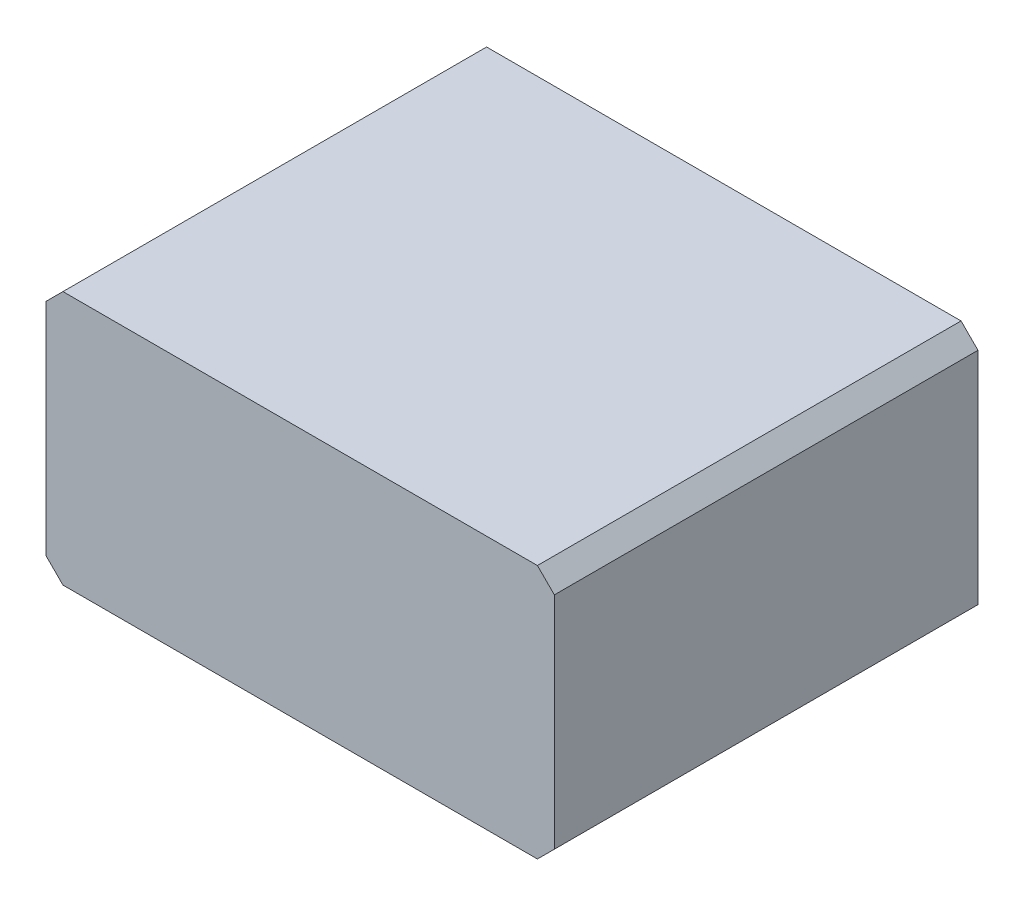
SolidWorks part; units mm, degrees
ref_plane "前视基准面" through (0, 0, 0) normal (0, 0, 1) x (1, 0, 0)
ref_plane "上视基准面" through (0, 0, 0) normal (0, 1, 0) x (1, 0, 0)
ref_plane "右视基准面" through (0, 0, 0) normal (1, 0, 0) x (0, 0, -1)
sketch "草图1" plane through (0, 0, 0) normal (0, 0, 1) x (1, 0, 0)
  line L1 (-30, 15) -> (30, 15)
  line L2 (-30, 15) -> (-30, -15)
  line L3 (-30, -15) -> (30, -15)
  line L4 (30, 15) -> (30, -15)
  line L5 (-30, 15) -> (30, -15) construction
  line L6 (-30, -15) -> (30, 15) construction
  point P0 (0, 0)
  dimension "D1" = 60
  dimension "D2" = 30
extrude "凸台-拉伸1" add sketch "草图1" along normal mid plane 50
chamfer "倒角1" distance 2 angle 45 4 edges at (-30, -15, 0) (-30, 15, 0) (30, -15, 0) (30, 15, 0)
equation "\"零件重量\"= \"SW-质量\""
